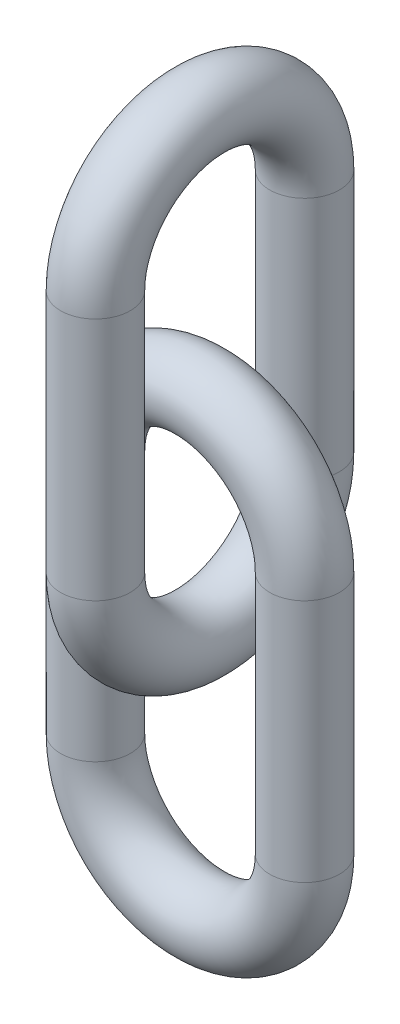
SolidWorks part; units mm, degrees
ref_plane "Front Plane" through (0, 0, 0) normal (0, 0, 1) x (1, 0, 0)
ref_plane "Top Plane" through (0, 0, 0) normal (0, 1, 0) x (1, 0, 0)
ref_plane "Right Plane" through (0, 0, 0) normal (1, 0, 0) x (0, 0, -1)
sketch "Sketch2" plane through (0, 0, 0) normal (1, 0, 0) x (0, 0, -1)
  line L0 (0, 70) -> (0, -70)
  line L2 (120, -70) -> (120, 70)
  arc A0 (0, -70) -> (120, -70) centre (60, -70) ccw
  arc A1 (120, 70) -> (0, 70) centre (60, 70) ccw
  point P4 (0, 0)
  dimension "D2" = 60
  dimension "D1" = 140
sweep "Sweep2" add path "Sketch2" circular profile diameter 40 parameters "D3"=40
ref_plane "Plane1" through (0, 0, -60) normal (0, 0, 1) x (1, 0, 0)
sketch "Sketch38" plane through (0, 0, -60) normal (0, 0, 1) x (1, 0, 0)
  line L0 (20, -70) -> (-20, -70) construction
  line L1 (60, -70) -> (60, -210)
  line L2 (-60, -210) -> (-60, -70)
  arc A0 (60, -70) -> (-60, -70) centre (0, -70) ccw
  arc A1 (60, -210) -> (-60, -210) centre (0, -210) cw
  dimension "D2" = 60
  dimension "D1" = 140
sweep "Sweep3" add path "Sketch38" circular profile diameter 40 parameters "D3"=40
